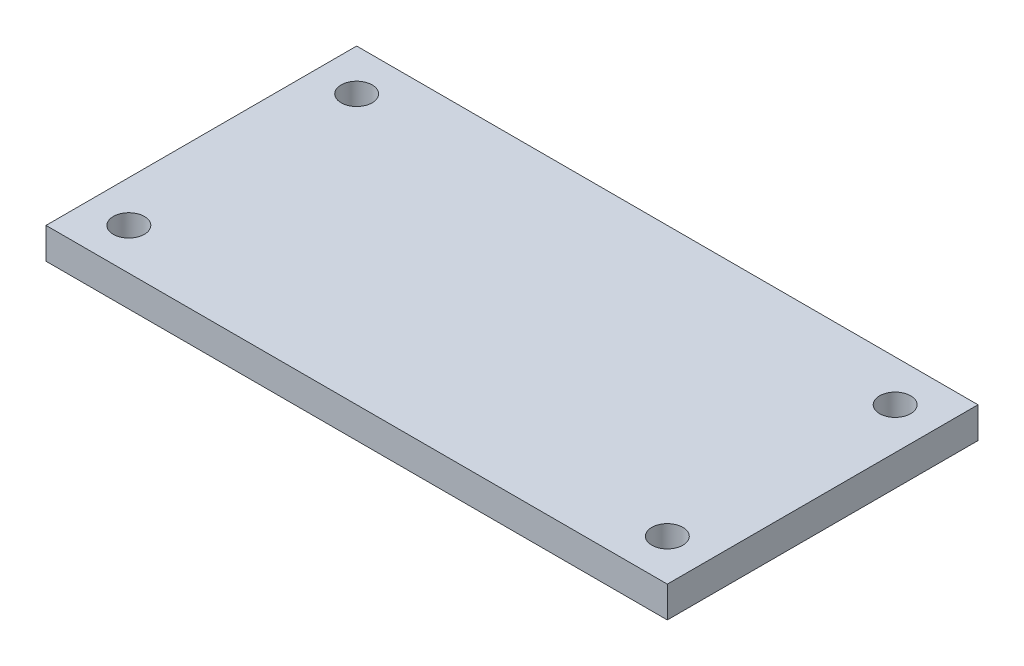
SolidWorks part; units mm, degrees
ref_plane "Alzado" through (0, 0, 0) normal (0, 0, 1) x (1, 0, 0)
ref_plane "Planta" through (0, 0, 0) normal (0, 1, 0) x (1, 0, 0)
ref_plane "Vista lateral" through (0, 0, 0) normal (1, 0, 0) x (0, 0, -1)
sketch "Croquis1" plane through (0, 0, 0) normal (0, 1, 0) x (1, 0, 0)
  line L0 (0, 0) -> (0, 25.0328) construction
  line L1 (0, 0) -> (34.7213, 0) construction
  line L2 (-30, 0) -> (-30, 15)
  line L3 (-30, 15) -> (0, 15)
  line L4 (0, 15) -> (30, 15)
  line L5 (30, 15) -> (30, 0)
  line L6 (30, 0) -> (30, -15)
  line L7 (30, -15) -> (-14.2623, -15)
  line L8 (-14.2623, -15) -> (-30, -15)
  line L9 (-30, -15) -> (-30, 0)
  circle A0 centre (-26, 11) radius 1.5
  circle A1 centre (26, 11) radius 1.5
  circle A2 centre (26, -11) radius 1.5
  circle A3 centre (-26, -11) radius 1.5
  dimension "D5" = 4
  dimension "D7" = 3
  dimension "D1" = 15
  dimension "D2" = 15
  dimension "D3" = 30
  dimension "D4" = 30
  dimension "D6" = 4
extrude "Saliente-Extruir1" add sketch "Croquis1" along normal blind 3
